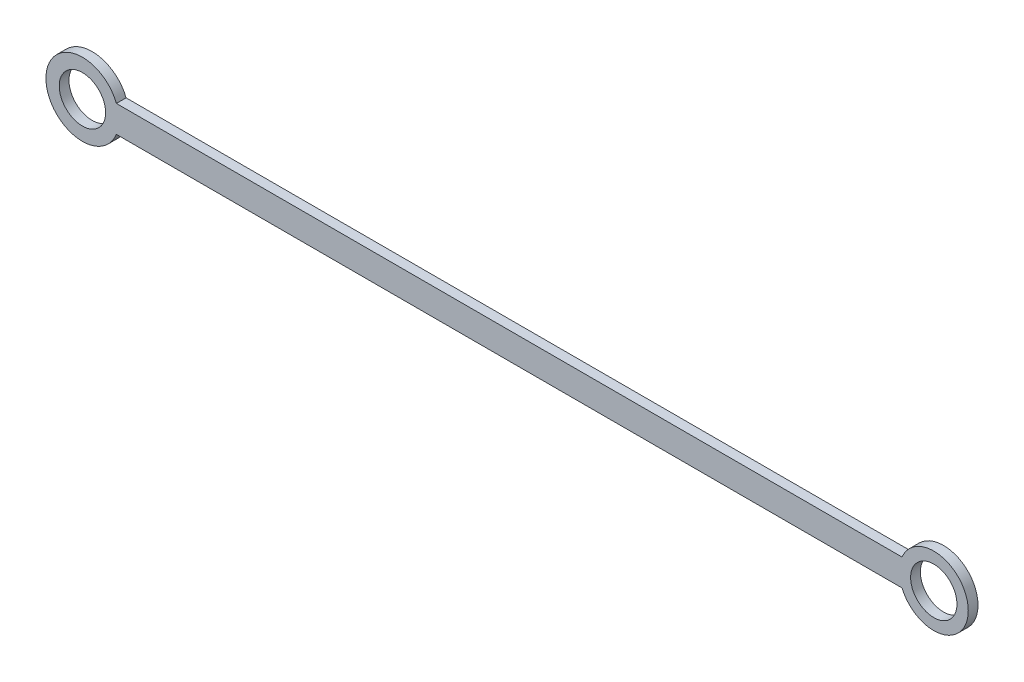
SolidWorks part; units mm, degrees
ref_plane "前视基准面" through (0, 0, 0) normal (0, 0, 1) x (1, 0, 0)
ref_plane "上视基准面" through (0, 0, 0) normal (0, 1, 0) x (1, 0, 0)
ref_plane "右视基准面" through (0, 0, 0) normal (1, 0, 0) x (0, 0, -1)
sketch "草图1" plane through (0, 0, 0) normal (0, 0, 1) x (1, 0, 0)
  line L0 (0, 0) -> (350, 0) construction
  line L6 (13.9553, 5.5) -> (336.9355, 5.5)
  line L8 (13.9553, -5.5) -> (336.9355, -5.5)
  circle A7 centre (0, 0) radius 9.53
  circle A8 centre (0, 0) radius 15 construction
  circle A9 centre (350, 0) radius 14.175 construction
  circle A10 centre (350, 0) radius 9.53
  arc A11 (13.9553, 5.5) -> (13.9553, -5.5) centre (0, 0) ccw
  arc A12 (336.9355, -5.5) -> (336.9355, 5.5) centre (350, 0) ccw
  dimension "D1" = 5.5
  dimension "D3" = 30
  dimension "D2" = 350
extrude "凸台-拉伸1" add sketch "草图1" along normal blind 4
